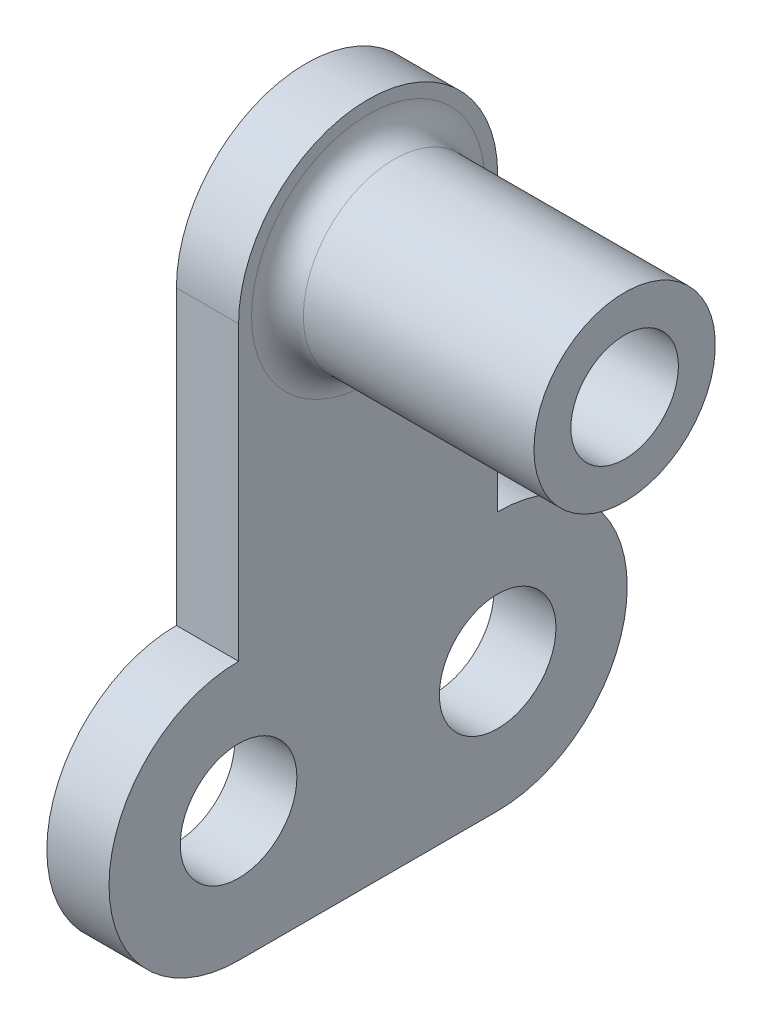
SolidWorks part; units mm, degrees
ref_plane "前视基准面" through (0, 0, 0) normal (0, 0, 1) x (1, 0, 0)
ref_plane "上视基准面" through (0, 0, 0) normal (0, 1, 0) x (1, 0, 0)
ref_plane "右视基准面" through (0, 0, 0) normal (1, 0, 0) x (0, 0, -1)
sketch "草图1" plane through (0, 0, 0) normal (1, 0, 0) x (0, 0, -1)
  line L0 (-5, 0) -> (5, 0)
  line L5 (-5, 10) -> (-5, 21.2822)
  line L6 (5, 10) -> (5, 21.2822)
  circle A2 centre (-5, 5) radius 2.25
  circle A3 centre (5, 5) radius 2.25
  arc A4 (-5, 10) -> (-5, 0) centre (-5, 5) ccw
  arc A6 (5, 0) -> (5, 10) centre (5, 5) ccw
  arc A10 (-5, 21.2822) -> (5, 21.2822) centre (0, 21.2822) cw
  circle A12 centre (0, 21.2822) radius 2.075
  dimension "D3" = 4.5
  dimension "D4" = 5
  dimension "D1" = 10
  dimension "D5" = 4.15
  dimension "D8" = 5
  dimension "D2" = 10
  dimension "D9" = 11.2822
extrude "凸台-拉伸1" add sketch "草图1" along normal blind 2.4
sketch "草图4" plane through (2.4, 0, 0) normal (1, 0, 0) x (0, 0, -1)
  circle A0 centre (0, 21.2822) radius 3.5
  circle A1 centre (0, 21.2822) radius 2.075 construction
  circle A2 centre (0, 21.2822) radius 2.075
  dimension "D1" = 7
extrude "凸台-拉伸2" add sketch "草图4" along normal blind 9.9
fillet "圆角1" radius 1 1 edges at (2.4, 21.2822, -3.5)
sketch "草图5" plane through (0, 0, 0) normal (-1, 0, 0) x (0, 0, 1)
  circle A0 centre (0, 21.2822) radius 1.2
  circle A1 centre (0, 21.2822) radius 2.075
extrude "凸台-拉伸3" add sketch "草图5" against normal blind 4
